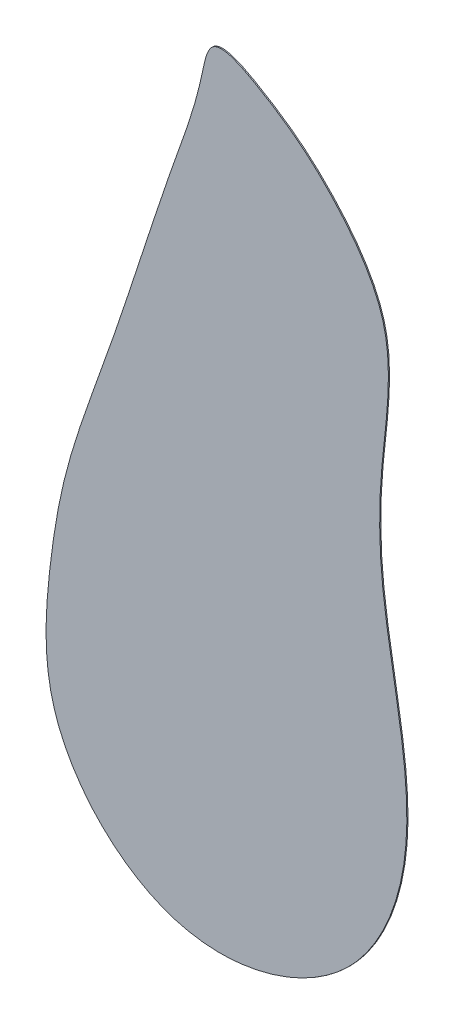
SolidWorks part; units mm, degrees
ref_plane "Front Plane" through (0, 0, 0) normal (0, 0, 1) x (1, 0, 0)
ref_plane "Top Plane" through (0, 0, 0) normal (0, 1, 0) x (1, 0, 0)
ref_plane "Right Plane" through (0, 0, 0) normal (1, 0, 0) x (0, 0, -1)
sketch "Sketch1" plane through (0, 0, 0) normal (0, 0, 1) x (1, 0, 0)
  line L0 (494.9871, 36.3192) -> (594.9832, 35.4439) construction
  spline S0 degree 3 poles (446.5136, 93.064) (400.2235, 70.9025) (346.8867, 74.7807) (302.8546, 119.3394) (305.8049, 176.8289) (313.6356, 226.6918) (337.0503, 287.2737) (356.6208, 351.8544) (372.9083, 394.8068) (378.0171, 424.5632) (408.5159, 408.5649) (431.7533, 389.8362) (455.0383, 359.534) (458.083, 324.7153) (452.8793, 293.0958) (452.8045, 251.444) (461.9718, 204.2349) (469.2317, 149.5941) (446.5136, 93.064) (400.2235, 70.9025) (346.8867, 74.7807) knots -0.205981 -0.134231 -0.06588 0 0.036614 0.124983 0.190635 0.23913 0.308968 0.42742 0.475733 0.491843 0.517228 0.564939 0.619604 0.643343 0.690633 0.735886 0.794019 0.865769 0.93412 1 1.036614 1.124983 1.190635 only from (391.9337, 73.4596) to (391.9337, 73.4596)
  spline S1 degree 3 poles (379.2721, 72.9822) (371.7986, 127.9397) (374.4058, 202.4634) (390.7072, 291.4266) (404.4325, 337.6476) (391.1263, 376.94) (389.331, 394.5046) (384.0986, 412.5933) (391.2758, 405.6481) (394.1926, 401.5683) (401.9626, 386.6601) (409.8478, 358.9621) (408.8349, 324.3733) (404.3307, 285.4887) (390.2031, 205.3631) (395.8442, 130.4954) (404.5871, 76.0182) knots 0 0 0 0 0.24425 0.324491 0.400115 0.452585 0.492113 0.499473 0.511274 0.515675 0.524006 0.583059 0.642032 0.674695 0.755841 1 1 1 1 construction
  dimension "D1" = 100
extrude "Boss-Extrude2" add sketch "Sketch1" along normal blind 0.5
sketch "Sketch6" plane through (0, 0, 0.5) normal (0, 0, 1) x (1, 0, 0)
  spline S0 degree 3 poles (2266.1909, -258.1429) (564.1644, -592.5928) (314.7807, -122.9353) (390.7072, 291.4266) (404.4325, 337.6476) (391.1263, 376.94) (389.331, 394.5046) (384.0986, 412.5933) (391.2758, 405.6481) (394.1926, 401.5683) (401.9626, 386.6601) (409.8478, 358.9621) (408.8349, 324.3733) (404.3307, 285.4887) (313.7393, -228.3062) (1118.5423, -834.1402) (-1484.1071, 538.1631) knots -1.463492 -1.463492 -1.463492 -1.463492 0.24425 0.324491 0.400115 0.452585 0.492113 0.499473 0.511274 0.515675 0.524006 0.583059 0.642032 0.674695 0.755841 2.937455 2.937455 2.937455 2.937455 only from (379.2721, 72.9822) to (404.5871, 76.0182) construction
  spline S1 degree 3 poles (379.2721, 72.9822) (371.7986, 127.9397) (374.4058, 202.4634) (390.7072, 291.4266) (404.4325, 337.6476) (391.1263, 376.94) (389.331, 394.5046) (384.0986, 412.5933) (391.2758, 405.6481) (394.1926, 401.5683) (401.9626, 386.6601) (409.8478, 358.9621) (408.8349, 324.3733) (404.3307, 285.4887) (390.2031, 205.3631) (395.8442, 130.4954) (404.5871, 76.0182) knots 0 0 0 0 0.24425 0.324491 0.400115 0.452585 0.492113 0.499473 0.511274 0.515675 0.524006 0.583059 0.642032 0.674695 0.755841 1 1 1 1
  spline S2 degree 2 poles (404.5871, 76.0182) (392.1743, 72.4471) (379.2721, 72.9822) knots 0 0 0 1 1 1
ref_plane "Plane1" through (0, 0, -0.7) normal (0, 0, -1) x (-1, 0, 0)
